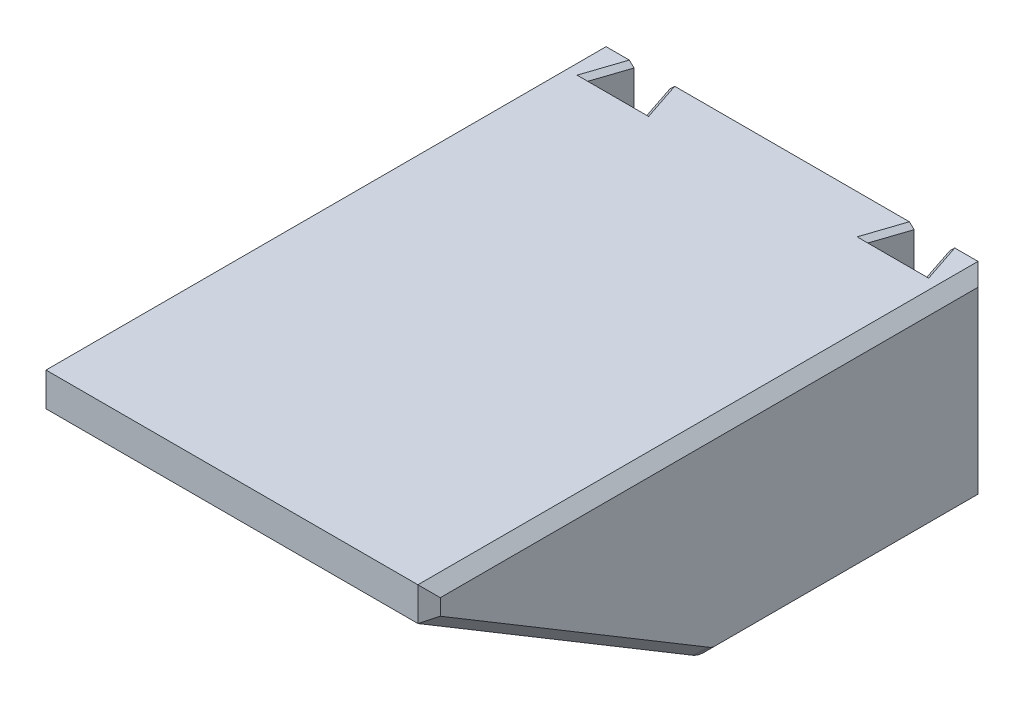
SolidWorks part; units mm, degrees
ref_plane "前视基准面" through (0, 0, 0) normal (0, 0, 1) x (1, 0, 0)
ref_plane "上视基准面" through (0, 0, 0) normal (0, 1, 0) x (1, 0, 0)
ref_plane "右视基准面" through (0, 0, 0) normal (1, 0, 0) x (0, 0, -1)
sketch "草图1" plane through (0, 0, 0) normal (0, 1, 0) x (1, 0, 0)
  line L1 (-7.6, -12.5) -> (7.6, -12.5)
  line L2 (-7.6, -12.5) -> (-7.6, 12.5)
  line L3 (-7.6, 12.5) -> (7.6, 12.5)
  line L4 (7.6, -12.5) -> (7.6, 12.5)
  line L5 (-7.6, -12.5) -> (7.6, 12.5) construction
  line L6 (-7.6, 12.5) -> (7.6, -12.5) construction
  point P0 (0, 0)
  dimension "D1" = 15.2
  dimension "D2" = 25
extrude "凸台-拉伸1" add sketch "草图1" along normal blind 3
sketch "草图4" plane through (-7.6, 0, 0) normal (-1, 0, 0) x (0, 0, 1)
  line L1 (-12.5, -15) -> (-12.5, 3)
  line L4 (12.5, 3) -> (12.5, 0)
  line L5 (-12.5, 3) -> (12.5, 3)
  line L6 (12.5, 0) -> (-12.5, -15)
  line L7 (12.5, 3) -> (12.5, 0) construction
  dimension "D1" = 3
  dimension "D2" = 18
  dimension "D3" = 25
extrude "凸台-拉伸3" add sketch "草图4" along normal blind 10
mirror "镜向4" about plane through (0, 0, 0) normal (1, 0, 0) of "凸台-拉伸3"
sketch "草图5" plane through (0, 0, -12.5) normal (0, 0, -1) x (-1, 0, 0)
  line L4 (7.6, 0) -> (7.6, -15)
  line L6 (7.6, 0) -> (7.6, -15)
  line L8 (-7.6, 0) -> (7.6, 0)
  line L12 (17.6, 3) -> (-17.6, 3)
  line L14 (7.6, -15) -> (17.6, -15)
  line L15 (7.6, -15) -> (17.6, -15)
  line L16 (-7.6, 0) -> (7.6, 0)
  line L20 (17.6, 3) -> (-17.6, 3)
  line L24 (17.6, -15) -> (17.6, 3)
  line L25 (17.6, -15) -> (17.6, 3)
  line L26 (-17.6, 3) -> (-17.6, -15)
  line L27 (-17.6, 3) -> (-17.6, -15)
  line L28 (-17.6, -15) -> (-7.6, -15)
  line L29 (-17.6, -15) -> (-7.6, -15)
  line L30 (-7.6, -15) -> (-7.6, 0)
  line L31 (-7.6, -15) -> (-7.6, 0)
  dimension "D1" = 0
extrude "凸台-拉伸4" add sketch "草图5" along normal blind 25
sketch "草图6" plane through (0, 3, 0) normal (0, 1, 0) x (1, 0, 0)
  line L0 (0, -2.1088) -> (0, 54.4181) construction
  line L1 (-17.6, 37.5) -> (17.6, 37.5) construction
  line L3 (14, 37.5) -> (11, 37.5) construction
  line L6 (15, 34.5) -> (10, 34.5) construction
  line L7 (14, 37.5) -> (15, 34.5) construction
  line L8 (11, 37.5) -> (10, 34.5) construction
  line L9 (12.5, 27.7234) -> (12.5, 39.7397) construction
  line L10 (14.0721, 37.6) -> (10.9279, 37.6)
  line L11 (10.9279, 37.6) -> (9.8613, 34.4)
  line L12 (15.1387, 34.4) -> (9.8613, 34.4)
  line L13 (14.0721, 37.6) -> (15.1387, 34.4)
  line L14 (-12.5, 27.7234) -> (-12.5, 39.7397) construction
  line L15 (-11, 37.5) -> (-10, 34.5) construction
  line L16 (-14, 37.5) -> (-15, 34.5) construction
  line L17 (-15, 34.5) -> (-10, 34.5) construction
  line L18 (-14, 37.5) -> (-11, 37.5) construction
  line L19 (-14.0721, 37.6) -> (-15.1387, 34.4)
  line L20 (-15.1387, 34.4) -> (-9.8613, 34.4)
  line L21 (-10.9279, 37.6) -> (-9.8613, 34.4)
  line L22 (-14.0721, 37.6) -> (-10.9279, 37.6)
  point P5 (12.5, 37.5)
  point P19 (-12.5, 37.5)
  point P20 (16.5424, 29.6309)
  dimension "D1" = 12.5
  dimension "D2" = 3
  dimension "D3" = 5
  dimension "D4" = 3
  dimension "D5" = 0.1
extrude "切除-拉伸1" cut sketch "草图6" against normal up to surface (18 mm away) up to face at (12.6, -15, -25)
fillet "圆角2" radius 2 2 edges at (-12.6, -15, -12.5) (12.6, -15, -12.5)
chamfer "倒角1" distance 1 angle 45 20 edges at (-7.6, -15, -25.277) (-7.6, -14.9274, -12.5201) (-7.6, -7.3575, 0.2375) (7.6, -15, -25.277) (7.6, -14.9274, -12.5201) (7.6, -7.3575, 0.2375) (-7.6, -7.5, -37.5) (7.6, -7.5, -37.5) (-17.6, -15, -25.277) (-17.6, -14.9274, -12.5201) (-17.6, -6, -37.5) (-17.6, 3, -12.5) (-17.6, -7.3575, 0.2375) (-17.6, 1.5, 12.5) (17.6, -15, -25.277) (17.6, -14.9274, -12.5201) (17.6, -6, -37.5) (17.6, 3, -12.5) (17.6, 1.5, 12.5) (17.6, -7.3575, 0.2375)
chamfer "倒角2" distance 0.4 angle 45 12 edges at (-10.3779, 3, -35.95) (-12.5, 3, -34.4) (-14.6221, 3, -35.95) (-14.6221, -15, -35.95) (-10.3779, -15, -35.95) (-12.5, -15, -34.4) (10.3779, 3, -35.95) (12.5, 3, -34.4) (14.6221, 3, -35.95) (10.3779, -15, -35.95) (12.5, -15, -34.4) (14.6221, -15, -35.95)
